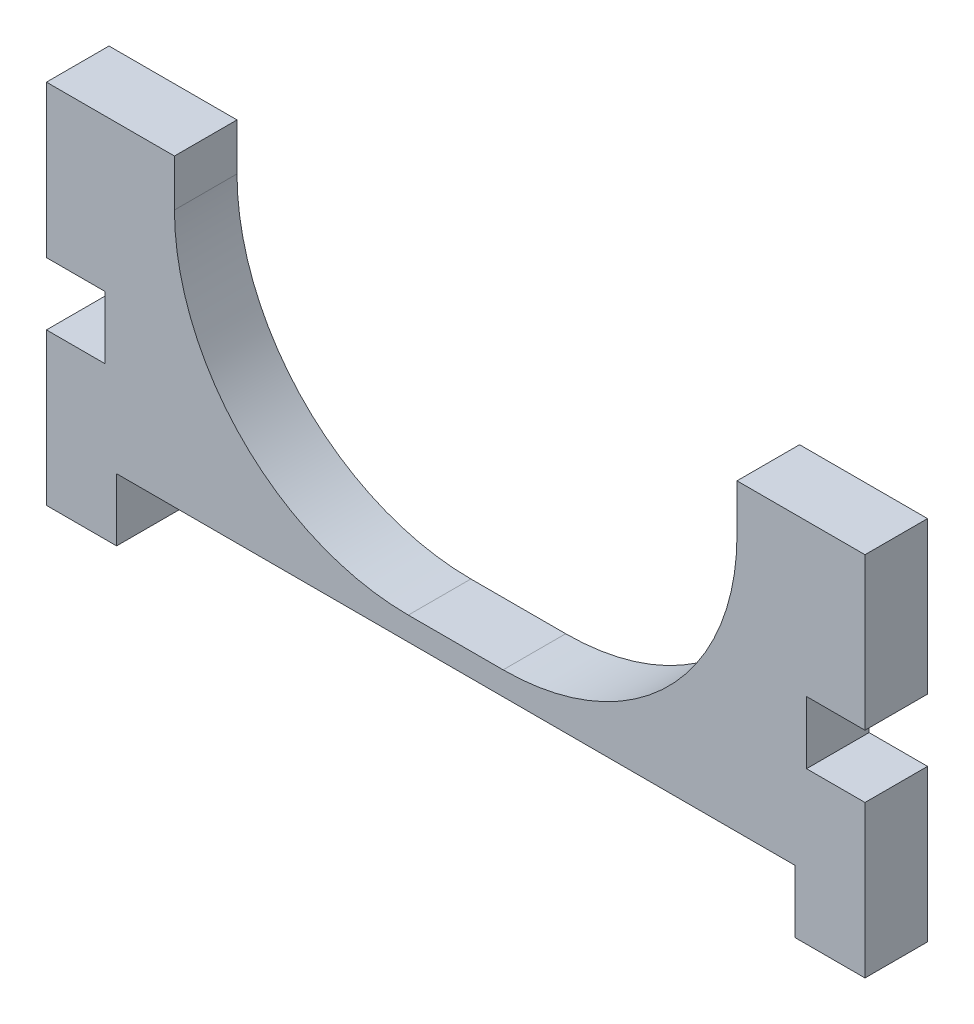
SolidWorks part; units mm, degrees
ref_plane "Front Plane" through (0, 0, 0) normal (0, 0, 1) x (1, 0, 0)
ref_plane "Top Plane" through (0, 0, 0) normal (0, 1, 0) x (1, 0, 0)
ref_plane "Right Plane" through (0, 0, 0) normal (1, 0, 0) x (0, 0, -1)
sketch "Model" plane through (0, 0, 0) normal (0, 0, 1) x (1, 0, 0)
  line L0 (39.055, 7.35) -> (30.945, 7.35)
  line L1 (59.055, 27.35) -> (59.055, 31.35)
  line L2 (59.055, 31.35) -> (70, 31.35)
  line L3 (70, 31.35) -> (70, 18.35)
  line L4 (70, 18.35) -> (65, 18.35)
  line L5 (65, 18.35) -> (65, 13)
  line L6 (65, 13) -> (70, 13)
  line L7 (70, 13) -> (70, 0)
  line L8 (70, 0) -> (64, 0)
  line L9 (64, 0) -> (64, 5.35)
  line L10 (6, 5.35) -> (64, 5.35)
  line L11 (6, 0) -> (6, 5.35)
  line L12 (0, 0) -> (6, 0)
  line L13 (0, 13) -> (0, 0)
  line L14 (5, 13) -> (0, 13)
  line L15 (5, 18.35) -> (5, 13)
  line L16 (0, 18.35) -> (5, 18.35)
  line L17 (0, 31.35) -> (0, 18.35)
  line L18 (10.945, 31.35) -> (0, 31.35)
  line L19 (10.945, 27.35) -> (10.945, 31.35)
  line L20 (35, -4.8933) -> (35, 38.7759) construction
  arc A0 (59.055, 27.35) -> (39.055, 7.35) centre (39.055, 27.35) cw
  arc A1 (10.945, 27.35) -> (30.945, 7.35) centre (30.945, 27.35) ccw
  point P7 (35, 7.35)
  point P28 (35, 5.35)
  dimension "D9" = 20
  dimension "D1" = 6
  dimension "D2" = 5.35
  dimension "D3" = 5
  dimension "D4" = 5.35
  dimension "D5" = 13
  dimension "D6" = 31.35
  dimension "D7" = 2
  dimension "D8" = 10.945
  dimension "D10" = 4
  dimension "D11" = 4.055
  dimension "D12" = 70
extrude "Boss-Extrude1" add sketch "Model" along normal blind 5.35
